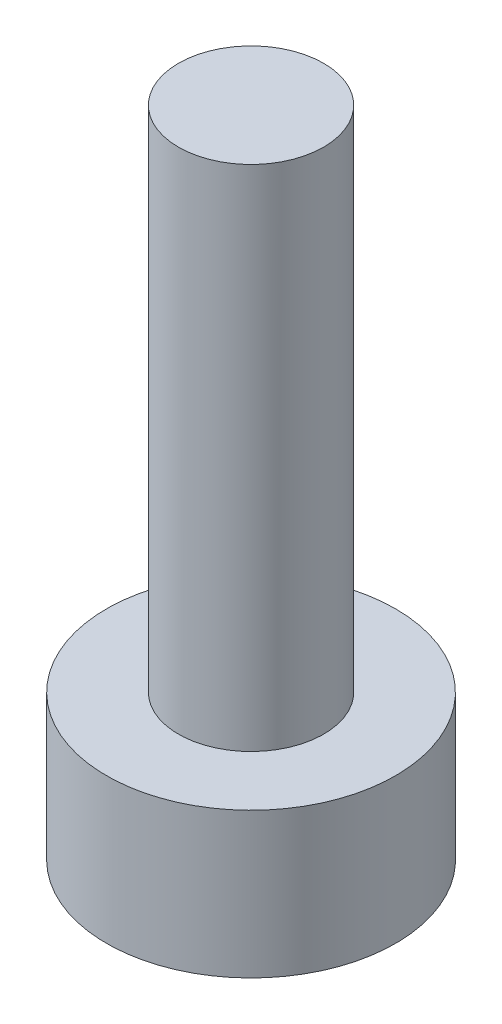
SolidWorks part; units mm, degrees
ref_plane "前视基准面" through (0, 0, 0) normal (0, 0, 1) x (1, 0, 0)
ref_plane "上视基准面" through (0, 0, 0) normal (0, 1, 0) x (1, 0, 0)
ref_plane "右视基准面" through (0, 0, 0) normal (1, 0, 0) x (0, 0, -1)
sketch "草图1" plane through (0, 0, 0) normal (0, 1, 0) x (1, 0, 0)
  circle A0 centre (0, 0) radius 1
  dimension "D1" = 2
extrude "凸台-拉伸1" add sketch "草图1" along normal blind 7
sketch "草图2" plane through (0, 0, 0) normal (0, -1, 0) x (1, 0, 0)
  circle A0 centre (0, 0) radius 1.99
  dimension "D1" = 3.98
extrude "凸台-拉伸2" add sketch "草图2" along normal blind 2
